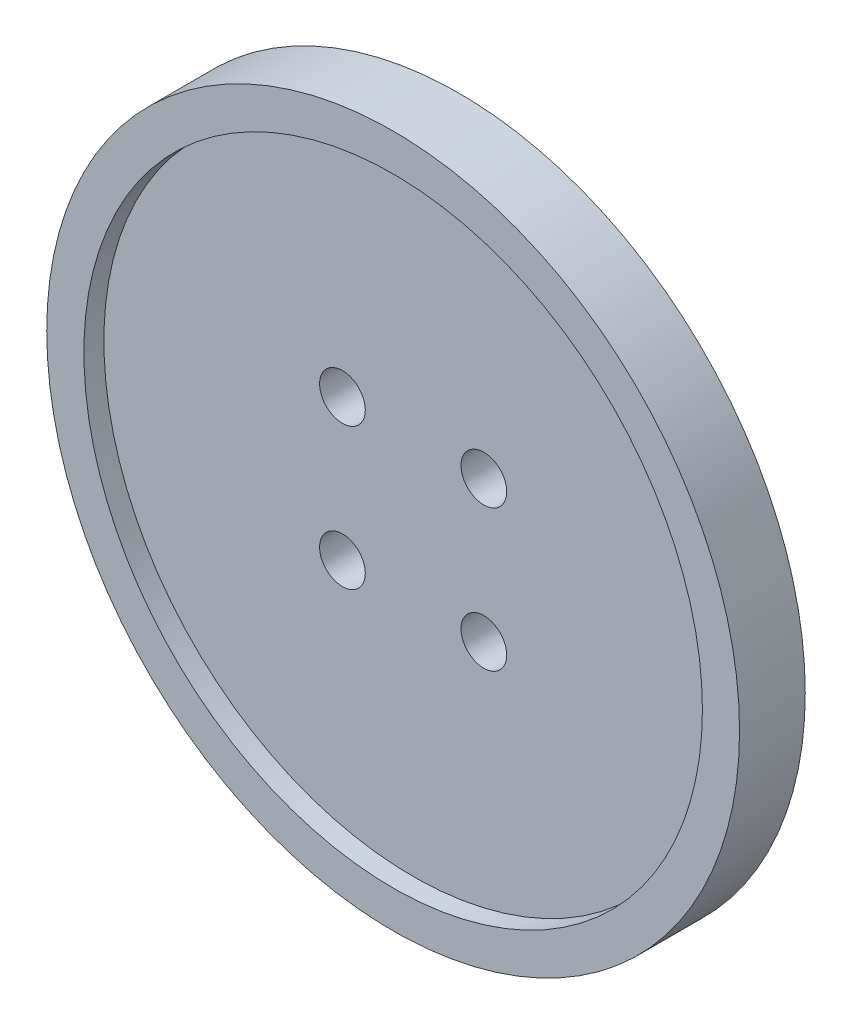
SolidWorks part; units mm, degrees
ref_plane "Front Plane" through (0, 0, 0) normal (0, 0, 1) x (1, 0, 0)
ref_plane "Top Plane" through (0, 0, 0) normal (0, 1, 0) x (1, 0, 0)
ref_plane "Right Plane" through (0, 0, 0) normal (1, 0, 0) x (0, 0, -1)
sketch "Sketch1" plane through (0, 0, 0) normal (0, 0, 1) x (1, 0, 0)
  line L1 (-4.9497, 4.9497) -> (4.9497, 4.9497) construction
  line L2 (-4.9497, 4.9497) -> (-4.9497, -4.9497) construction
  line L3 (-4.9497, -4.9497) -> (4.9497, -4.9497) construction
  line L4 (4.9497, 4.9497) -> (4.9497, -4.9497) construction
  line L5 (-4.9497, 4.9497) -> (4.9497, -4.9497) construction
  line L6 (-4.9497, -4.9497) -> (4.9497, 4.9497) construction
  circle A0 centre (0, 0) radius 24.25
  circle A1 centre (-4.9497, 4.9497) radius 1.6
  circle A2 centre (4.9497, 4.9497) radius 1.6
  circle A3 centre (4.9497, -4.9497) radius 1.6
  circle A4 centre (-4.9497, -4.9497) radius 1.6
  dimension "D1" = 48.5
  dimension "D3" = 3.2
  dimension "D2" = 14
extrude "Boss-Extrude1" add sketch "Sketch1" along normal blind 4.6
sketch "Sketch2" plane through (0, 0, 4.6) normal (0, 0, 1) x (1, 0, 0)
  circle A0 centre (0, 0) radius 21.65
  circle A1 centre (0, 0) radius 24.25 construction
  point P4 (0, 0)
  dimension "D1" = 2.6
extrude "Cut-Extrude1" cut sketch "Sketch2" against normal blind 1.4 contours A0
